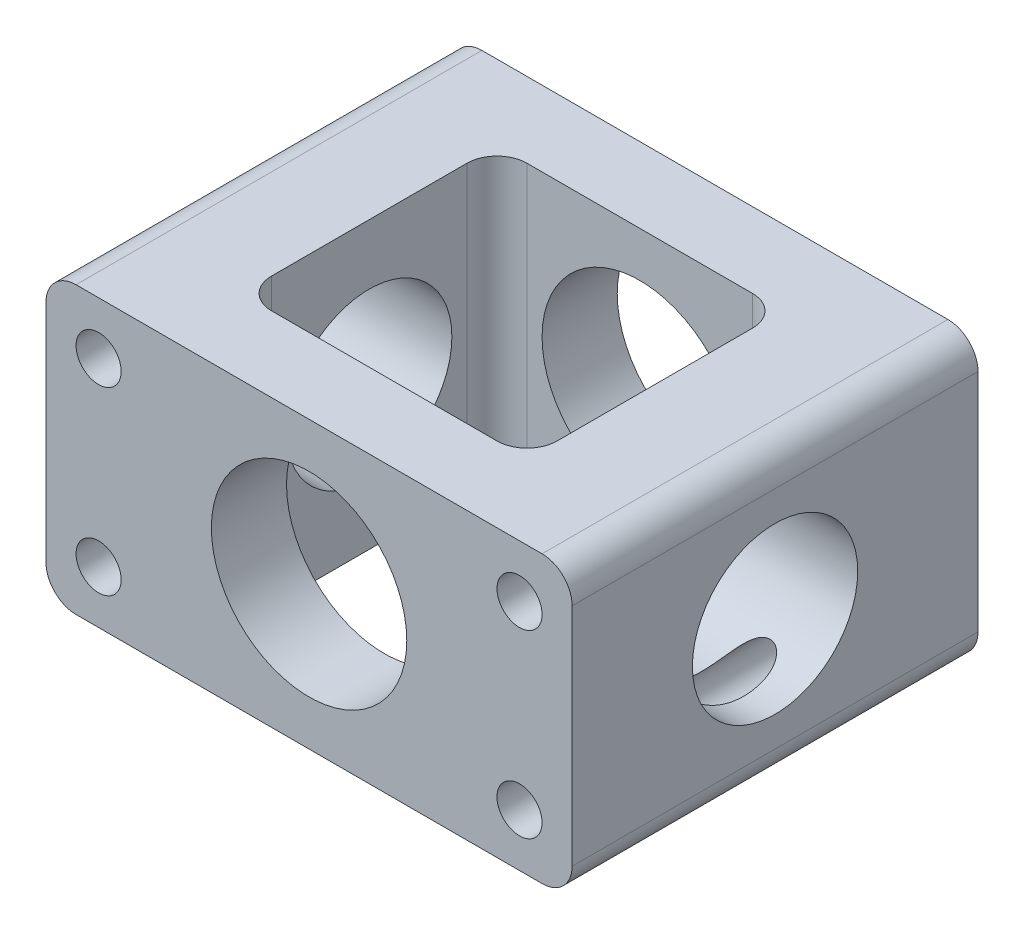
SolidWorks part; units mm, degrees
material "POM 乙缩醛共聚物"
ref_plane "前视基准面" through (0, 0, 0) normal (0, 0, 1) x (1, 0, 0)
ref_plane "上视基准面" through (0, 0, 0) normal (0, 1, 0) x (1, 0, 0)
ref_plane "右视基准面" through (0, 0, 0) normal (1, 0, 0) x (0, 0, -1)
sketch "草图1" plane through (0, 0, 0) normal (0, 0, 1) x (1, 0, 0)
  line L1 (-17.5, 9.5) -> (17.5, 9.5)
  line L2 (-17.5, 9.5) -> (-17.5, -9.5)
  line L3 (-17.5, -9.5) -> (17.5, -9.5)
  line L4 (17.5, 9.5) -> (17.5, -9.5)
  line L5 (-17.5, 9.5) -> (17.5, -9.5) construction
  line L6 (-17.5, -9.5) -> (17.5, 9.5) construction
  line L7 (-14, 6) -> (14, 6) construction
  line L8 (-14, 6) -> (-14, -6) construction
  line L9 (-14, -6) -> (14, -6) construction
  line L10 (14, 6) -> (14, -6) construction
  line L11 (-14, 6) -> (14, -6) construction
  line L12 (-14, -6) -> (14, 6) construction
  circle A0 centre (-14, 6) radius 1.5
  circle A1 centre (14, 6) radius 1.5
  circle A2 centre (14, -6) radius 1.5
  circle A3 centre (-14, -6) radius 1.5
  point P0 (0, 0)
  point P5 (0, 0)
  dimension "D5" = 3
  dimension "D6" = 3
  dimension "D7" = 3
  dimension "D8" = 3
  dimension "D1" = 19
  dimension "D2" = 35
  dimension "D3" = 12
  dimension "D4" = 28
extrude "凸台-拉伸1" add sketch "草图1" along normal blind 27
sketch "草图2" plane through (0, -9.5, 0) normal (0, -1, 0) x (1, 0, 0)
  line L0 (-17.5, 27) -> (17.5, 27) construction
  line L1 (-9.5, 22) -> (9.5, 22)
  line L2 (-9.5, 22) -> (-9.5, 5)
  line L3 (-9.5, 5) -> (9.5, 5)
  line L4 (9.5, 22) -> (9.5, 5)
  line L5 (-9.5, 22) -> (9.5, 5) construction
  line L6 (-9.5, 5) -> (9.5, 22) construction
  line L7 (17.5, 27) -> (17.5, 0) construction
  line L8 (-17.5, 27) -> (-17.5, 0) construction
  line L9 (-17.5, 0) -> (17.5, 0) construction
  point P0 (0, 13.5)
  dimension "D1" = 5
  dimension "D2" = 8
  dimension "D3" = 8
  dimension "D4" = 5
extrude "切除-拉伸1" cut sketch "草图2" against normal through all
sketch "草图3" plane through (-17.5, 0, 0) normal (-1, 0, 0) x (0, 0, 1)
  circle A0 centre (13.5, 0) radius 5.5
  dimension "D1" = 11
extrude "切除-拉伸2" cut sketch "草图3" against normal through all
sketch "草图4" plane through (0, 0, 27) normal (0, 0, 1) x (1, 0, 0)
  circle A0 centre (0, 0) radius 6.5
  dimension "D1" = 13
extrude "切除-拉伸3" cut sketch "草图4" against normal through all
fillet "圆角1" radius 2 4 edges at (-9.5, 0, 5) (-9.5, 0, 22) (9.5, 0, 5) (9.5, 0, 22)
fillet "圆角2" radius 2 4 edges at (17.5, -9.5, 13.5) (-17.5, 9.5, 13.5) (17.5, 9.5, 13.5) (-17.5, -9.5, 13.5)
extrude "切除-拉伸4" cut sketch "草图5" against normal through all
sketch "草图5" plane through (-4.2179, -201.0156, 33) normal (0, 0, 1) x (1, 0, 0)
  line L1 (-131.7821, 206.0156) -> (-111.7821, 206.0156)
  line L2 (-131.7821, 206.0156) -> (-131.7821, 196.0156)
  line L3 (-131.7821, 196.0156) -> (-111.7821, 196.0156)
  line L4 (-111.7821, 206.0156) -> (-111.7821, 196.0156)
  line L5 (-131.7821, 206.0156) -> (-111.7821, 196.0156) construction
  line L6 (-131.7821, 196.0156) -> (-111.7821, 206.0156) construction
  line L7 (-5.7821, 206.0156) -> (14.2179, 206.0156)
  line L8 (-5.7821, 206.0156) -> (-5.7821, 196.0156)
  line L9 (-5.7821, 196.0156) -> (14.2179, 196.0156)
  line L10 (14.2179, 206.0156) -> (14.2179, 196.0156)
  line L11 (-5.7821, 206.0156) -> (14.2179, 196.0156) construction
  line L12 (-5.7821, 196.0156) -> (14.2179, 206.0156) construction
  line L16 (-135.7821, 207.0156) -> (-107.7821, 207.0156) construction
  line L17 (-135.7821, 207.0156) -> (-135.7821, 195.0156) construction
  line L18 (-135.7821, 195.0156) -> (-107.7821, 195.0156) construction
  line L19 (-107.7821, 207.0156) -> (-107.7821, 195.0156) construction
  line L20 (-135.7821, 207.0156) -> (-107.7821, 195.0156) construction
  line L21 (-135.7821, 195.0156) -> (-107.7821, 207.0156) construction
  line L22 (-9.7821, 207.0156) -> (18.2179, 207.0156) construction
  line L23 (-9.7821, 207.0156) -> (-9.7821, 195.0156) construction
  line L24 (-9.7821, 195.0156) -> (18.2179, 195.0156) construction
  line L25 (18.2179, 207.0156) -> (18.2179, 195.0156) construction
  line L26 (-9.7821, 207.0156) -> (18.2179, 195.0156) construction
  line L27 (-9.7821, 195.0156) -> (18.2179, 207.0156) construction
  line L28 (-135.7821, 190.5156) -> (-107.7821, 190.5156)
  line L29 (-135.7821, 190.5156) -> (-135.7821, 148.5156)
  line L30 (-135.7821, 148.5156) -> (-107.7821, 148.5156)
  line L31 (-107.7821, 190.5156) -> (-107.7821, 148.5156)
  line L32 (-135.7821, 190.5156) -> (-107.7821, 148.5156) construction
  line L33 (-135.7821, 148.5156) -> (-107.7821, 190.5156) construction
  line L34 (-9.7821, 190.5156) -> (18.2179, 190.5156)
  line L35 (-9.7821, 190.5156) -> (-9.7821, 148.5156)
  line L36 (-9.7821, 148.5156) -> (18.2179, 148.5156)
  line L37 (18.2179, 190.5156) -> (18.2179, 148.5156)
  line L38 (-9.7821, 190.5156) -> (18.2179, 148.5156) construction
  line L39 (-9.7821, 148.5156) -> (18.2179, 190.5156) construction
  circle A0 centre (-135.7821, 207.0156) radius 1.5
  circle A1 centre (-135.7821, 195.0156) radius 1.5
  circle A2 centre (-107.7821, 207.0156) radius 1.5
  circle A3 centre (-107.7821, 195.0156) radius 1.5
  circle A4 centre (18.2179, 207.0156) radius 1.5
  circle A5 centre (18.2179, 195.0156) radius 1.5
  circle A6 centre (-9.7821, 207.0156) radius 1.5
  circle A7 centre (-9.7821, 195.0156) radius 1.5
  point P0 (-121.7821, 201.0156)
  point P5 (4.2179, 201.0156)
  point P16 (-121.7821, 201.0156)
  point P21 (4.2179, 201.0156)
  point P34 (-121.7821, 169.5156)
  point P39 (4.2179, 169.5156)
